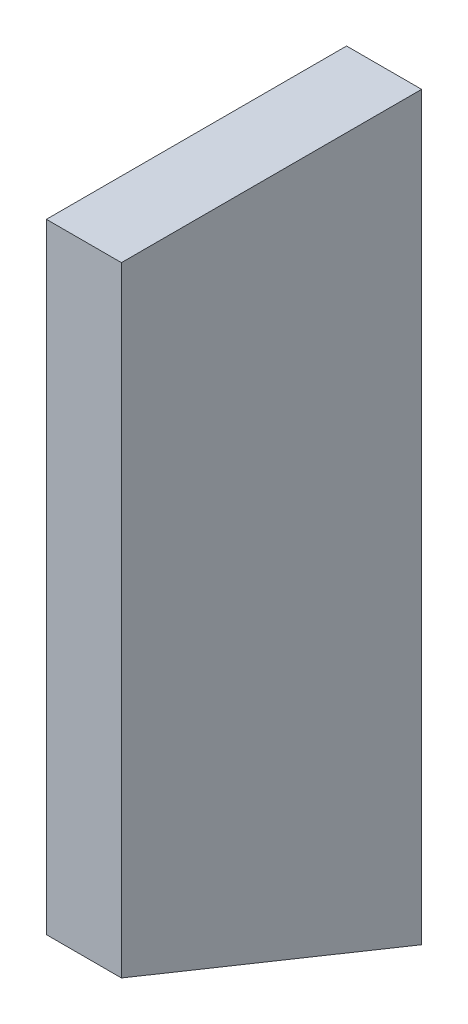
SolidWorks part; units mm, degrees
material "MDF"
ref_plane "Front" through (0, 0, 0) normal (0, 0, 1) x (1, 0, 0)
ref_plane "Top" through (0, 0, 0) normal (0, 1, 0) x (1, 0, 0)
ref_plane "Right" through (0, 0, 0) normal (1, 0, 0) x (0, 0, -1)
sketch "Sketch2" plane through (475.0459, 0, 0) normal (-1, 0, 0) x (0, 0, 1)
  line L1 (11.7614, 6983.73) -> (-445.4386, 6983.73) construction
  line L2 (11.7614, 6983.73) -> (-64.4386, 6983.73)
  line L3 (11.7614, 6983.73) -> (11.7614, 6826.4627)
  line L4 (11.7614, 6826.4627) -> (-64.4386, 6795.6759)
  line L5 (-64.4386, 6983.73) -> (-64.4386, 6795.6759)
  line L6 (11.7614, 6826.4627) -> (11.7614, 6983.73) construction
  line L7 (-445.4386, 6641.7419) -> (11.7614, 6826.4627) construction
  dimension "D1" = 76.2
extrude "Boss-Extrude1" add sketch "Sketch2" along normal blind 19.05
